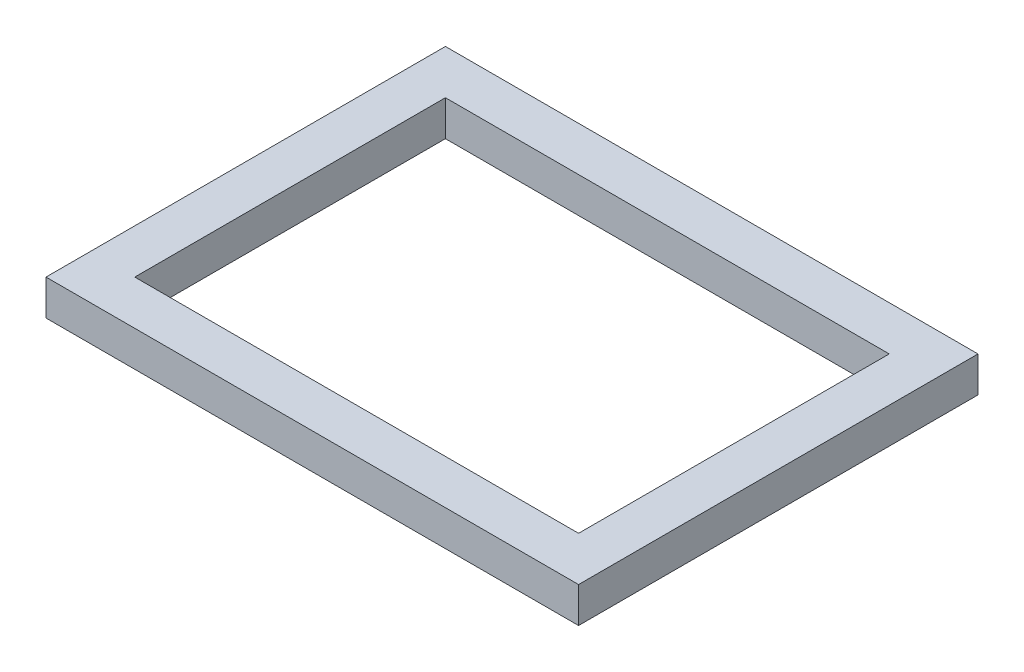
SolidWorks part; units mm, degrees
ref_plane "Front Plane" through (0, 0, 0) normal (0, 0, 1) x (1, 0, 0)
ref_plane "Top Plane" through (0, 0, 0) normal (0, 1, 0) x (1, 0, 0)
ref_plane "Right Plane" through (0, 0, 0) normal (1, 0, 0) x (0, 0, -1)
sketch "Sketch1" plane through (0, 0, 0) normal (0, 1, 0) x (1, 0, 0)
  line L1 (-15.875, -11.1125) -> (15.875, -11.1125)
  line L2 (-15.875, -11.1125) -> (-15.875, 11.1125)
  line L3 (-15.875, 11.1125) -> (15.875, 11.1125)
  line L4 (15.875, -11.1125) -> (15.875, 11.1125)
  line L5 (-15.875, -11.1125) -> (15.875, 11.1125) construction
  line L6 (-15.875, 11.1125) -> (15.875, -11.1125) construction
  line L7 (-19.05, 14.2875) -> (19.05, 14.2875)
  line L8 (-19.05, 14.2875) -> (-19.05, -14.2875)
  line L9 (-19.05, -14.2875) -> (19.05, -14.2875)
  line L10 (19.05, 14.2875) -> (19.05, -14.2875)
  line L11 (-19.05, 14.2875) -> (19.05, -14.2875) construction
  line L12 (-19.05, -14.2875) -> (19.05, 14.2875) construction
  point P0 (0, 0)
  point P6 (0, 0)
  dimension "D1" = 31.75
  dimension "D2" = 22.225
  dimension "D3" = 3.175
  dimension "D4" = 3.175
extrude "Boss-Extrude1" add sketch "Sketch1" along normal blind 2.54
